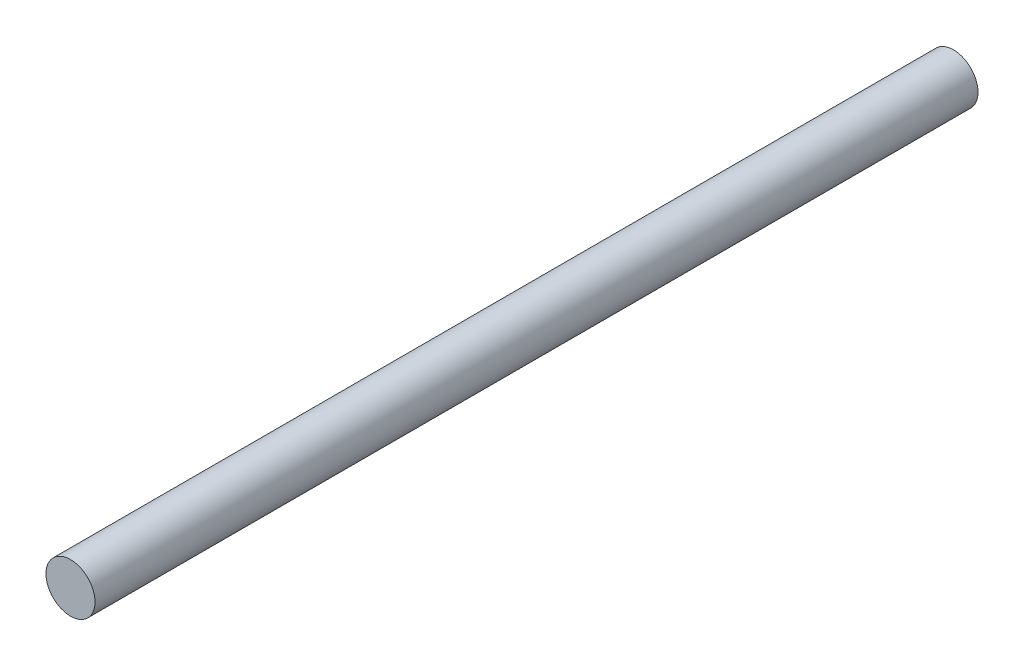
SolidWorks part; units mm, degrees
ref_plane "Plan de face" through (0, 0, 0) normal (0, 0, 1) x (1, 0, 0)
ref_plane "Plan de dessus" through (0, 0, 0) normal (0, 1, 0) x (1, 0, 0)
ref_plane "Plan de droite" through (0, 0, 0) normal (1, 0, 0) x (0, 0, -1)
sketch "Esquisse1" plane through (0, 0, 0) normal (0, 0, 1) x (1, 0, 0)
  circle A0 centre (0, 0) radius 2.5
  dimension "D1" = 5
extrude "Boss.-Extru.1" add sketch "Esquisse1" against normal blind 90
